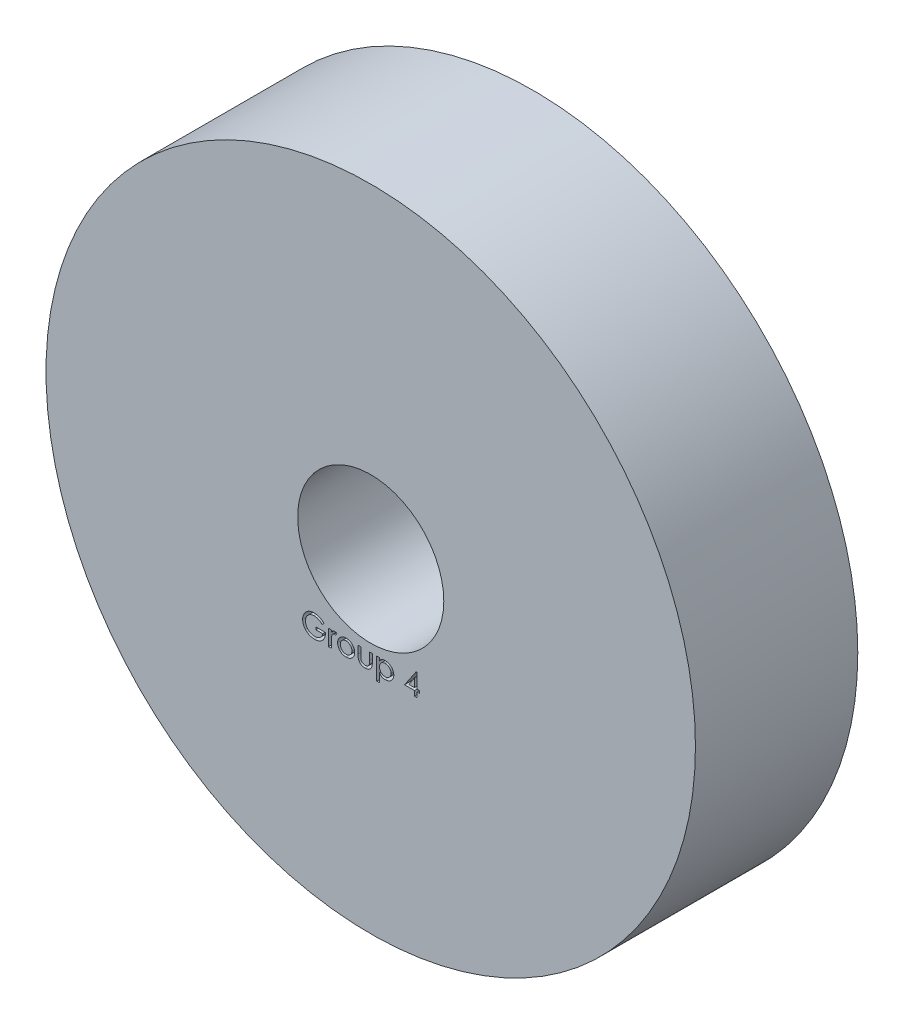
SolidWorks part; units mm, degrees
ref_plane "Front Plane" through (0, 0, 0) normal (0, 0, 1) x (1, 0, 0)
ref_plane "Top Plane" through (0, 0, 0) normal (0, 1, 0) x (1, 0, 0)
ref_plane "Right Plane" through (0, 0, 0) normal (1, 0, 0) x (0, 0, -1)
sketch "Sketch1" plane through (0, 0, 0) normal (0, 0, 1) x (1, 0, 0)
  circle A0 centre (0, 0) radius 20
  circle A1 centre (0, 0) radius 4.5
  dimension "D1" = 40
  dimension "D2" = 9
extrude "Boss-Extrude1" add sketch "Sketch1" along normal blind 10
sketch "Sketch2" plane through (0, 0, 10) normal (0, 0, 1) x (1, 0, 0)
  text T0 "<b>Group 4</b>" font "Century Gothic" height in points 5
extrude "Cut-Extrude1" cut sketch "Sketch2" against normal blind 1
